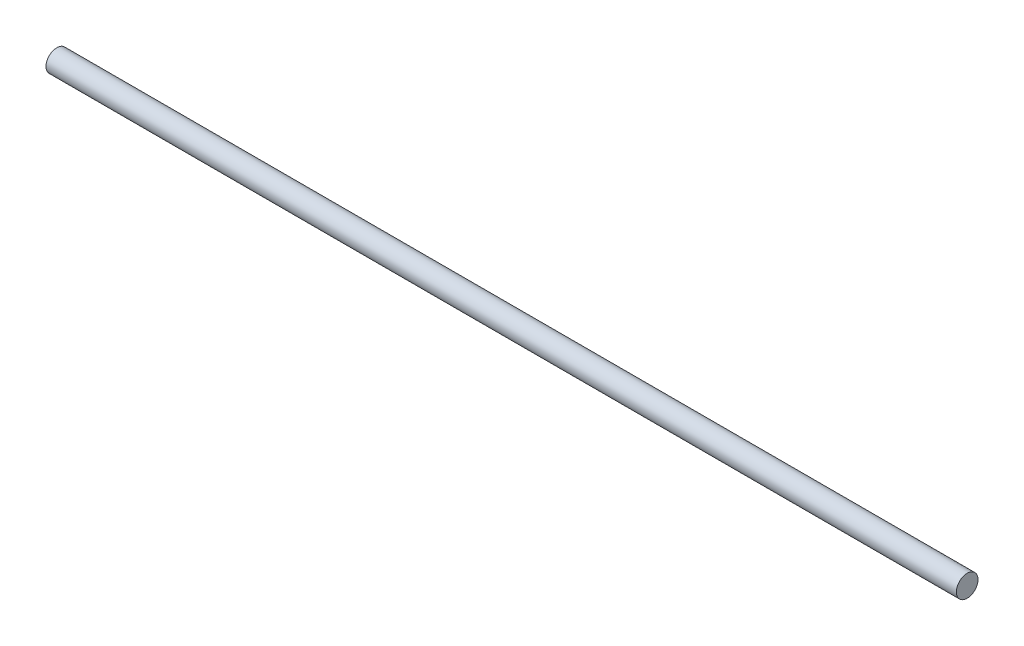
SolidWorks part; units mm, degrees
material "6061-T6 (SS)"
ref_plane "Front Plane" through (0, 0, 0) normal (0, 0, 1) x (1, 0, 0)
ref_plane "Top Plane" through (0, 0, 0) normal (0, 1, 0) x (1, 0, 0)
ref_plane "Right Plane" through (0, 0, 0) normal (1, 0, 0) x (0, 0, -1)
sketch "Sketch1" plane through (0, 0, 0) normal (1, 0, 0) x (0, 0, -1)
  circle A0 centre (0, 0) radius 2.286
  dimension "D1" = 4.572
extrude "Boss-Extrude1" add sketch "Sketch1" along normal blind 191.7509 contours A0
equation "\"r\"= .09'radius of the cross section [in]"
equation "\"Area\"= pi * \"r\" ^ 2'Area of the cross section [in^2]"
equation "\"F\"= 300'Load [Lb]"
equation "\"del\"= .0089'Max Delection [in]"
equation "\"E\"= 1 * 10 ^ 7'Youngs Mod of Al [psi]"
equation "\"L\"= \"del\" * \"Area\" * \"E\" / \"F\"'Designed Length [in]"
equation "\"D1@Sketch1\"=\"r\" *2"
equation "\"D1@Boss-Extrude1\"=\"L\""
